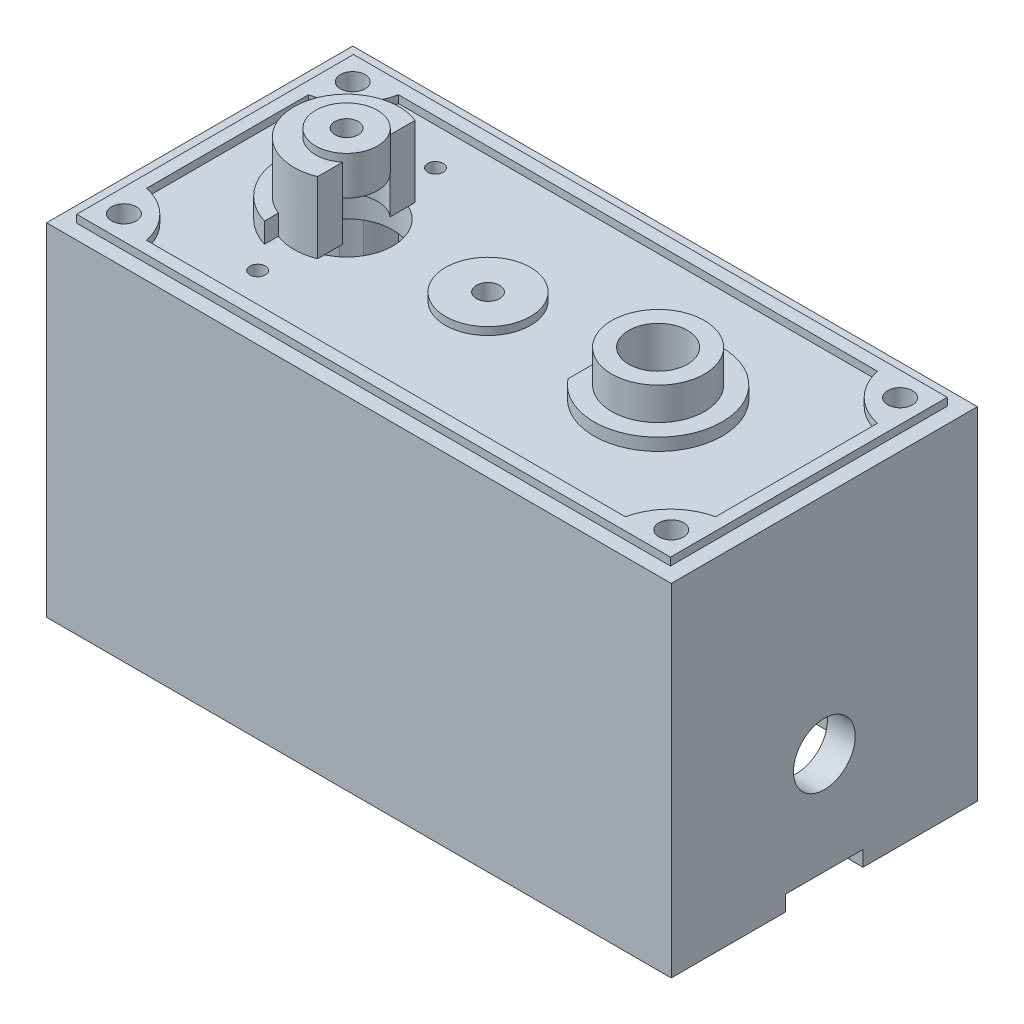
SolidWorks part; units mm, degrees
ref_plane "前基準面" through (0, 0, 0) normal (0, 0, 1) x (1, 0, 0)
ref_plane "上基準面" through (0, 0, 0) normal (0, 1, 0) x (1, 0, 0)
ref_plane "右基準面" through (0, 0, 0) normal (1, 0, 0) x (0, 0, -1)
sketch "草圖1" plane through (0, 0, 0) normal (0, 0, 1) x (1, 0, 0)
  line L1 (-20.2, 10.8) -> (20.2, 10.8)
  line L2 (-20.2, 10.8) -> (-20.2, -10.8)
  line L3 (-20.2, -10.8) -> (20.2, -10.8)
  line L4 (20.2, 10.8) -> (20.2, -10.8)
  line L5 (-20.2, 10.8) -> (20.2, -10.8) construction
  line L6 (-20.2, -10.8) -> (20.2, 10.8) construction
  point P0 (0, 0)
  dimension "D1" = 40.4
  dimension "D2" = 21.6
extrude "伸長1" add sketch "草圖1" along normal blind 19.8
sketch "草圖3" plane through (0, 10.8, 0) normal (0, 1, 0) x (1, 0, 0)
  line L0 (0, 0) -> (0, -19.8) construction
  line L1 (-19.2, -0.95) -> (19.2, -0.95)
  line L2 (-19.2, -0.95) -> (-19.2, -18.85)
  line L3 (-19.2, -18.85) -> (19.2, -18.85)
  line L4 (19.2, -0.95) -> (19.2, -18.85)
  line L5 (-19.2, -0.95) -> (19.2, -18.85) construction
  line L6 (-19.2, -18.85) -> (19.2, -0.95) construction
  line L7 (20.2, 0) -> (-20.2, 0) construction
  line L8 (20.2, -19.8) -> (-20.2, -19.8) construction
  line L9 (20.2, -9.9) -> (-20.2, -9.9) construction
  line L10 (20.2, -19.8) -> (20.2, 0) construction
  line L11 (-20.2, -19.8) -> (-20.2, 0) construction
  line L12 (-15.4852, -1.75) -> (15.4852, -1.75)
  line L13 (-15.4852, -18.05) -> (15.4852, -18.05)
  line L14 (-18.4, -4.6648) -> (-18.4, -15.1352)
  line L16 (18.4, -4.6648) -> (18.4, -15.1352)
  arc A0 (-18.4, -4.6648) -> (-15.4852, -1.75) centre (-19.2, -0.95) ccw
  arc A1 (-18.4, -15.1352) -> (-15.4852, -18.05) centre (-19.2, -18.85) cw
  arc A2 (15.4852, -1.75) -> (18.4, -4.6648) centre (19.2, -0.95) ccw
  arc A3 (18.4, -15.1352) -> (15.4852, -18.05) centre (19.2, -18.85) ccw
  point P0 (0, -9.9)
  point P17 (0, -9.9)
  dimension "D5" = 3.8
  dimension "D1" = 38.4
  dimension "D2" = 17.9
  dimension "D3" = 0.8
  dimension "D4" = 0.8
  dimension "D6" = 0.8
  dimension "D7" = 0.8
extrude "伸長2" add sketch "草圖3" along normal blind 1
sketch "草圖4" plane through (0, 10.8, 0) normal (0, 1, 0) x (1, 0, 0)
  line L4 (20.2, 0) -> (-20.2, 0)
  line L5 (20.2, 0) -> (-20.2, 0)
  line L6 (-20.2, 0) -> (-20.2, -19.8)
  line L7 (-20.2, 0) -> (-20.2, -19.8)
  line L8 (-20.2, -19.8) -> (20.2, -19.8)
  line L9 (-20.2, -19.8) -> (20.2, -19.8)
  line L10 (20.2, -19.8) -> (20.2, 0)
  line L11 (20.2, -19.8) -> (20.2, 0)
  dimension "D1" = 0
extrude "伸長3" add sketch "草圖4" along normal blind 0.5
sketch "草圖5" plane through (0, 11.3, 0) normal (0, 1, 0) x (1, 0, 0)
  line L0 (-20.2, -9.9) -> (20.2, -9.9) construction
  line L1 (-20.2, 0) -> (-20.2, -19.8) construction
  line L2 (20.2, -19.8) -> (20.2, 0) construction
  line L3 (19.2, -18.85) -> (19.2, -0.95) construction
  circle A0 centre (-1.55, -9.9) radius 2.75
  dimension "D1" = 5.5
  dimension "D3" = 20.75
sketch "草圖6" plane through (0, 11.3, 0) normal (0, 1, 0) x (1, 0, 0)
  line L0 (6.2, -7.3193) -> (6.2, -12.4807)
  line L1 (-20.2, -9.9) -> (20.2, -9.9) construction
  line L3 (19.2, -18.85) -> (19.2, -0.95) construction
  arc A0 (6.2, -12.4807) -> (6.2, -7.3193) centre (9.45, -9.9) ccw
  dimension "D1" = 4.15
  dimension "D2" = 3.25
  dimension "D3" = 13
extrude "伸長4" add sketch "草圖5" along normal blind 0.5
extrude "伸長5" add sketch "草圖6" along normal blind 0.8
sketch "草圖7" plane through (0, 12.1, 0) normal (0, 1, 0) x (1, 0, 0)
  circle A0 centre (9.45, -9.9) radius 3
  dimension "D1" = 6
extrude "伸長6" add sketch "草圖7" along normal blind 2.1
sketch "草圖8" plane through (0, 14.2, 0) normal (0, 1, 0) x (1, 0, 0)
  circle A0 centre (9.45, -9.9) radius 1.9
  dimension "D1" = 3.8
extrude "伸長7" cut sketch "草圖8" against normal through all
sketch "草圖10" plane through (0, 11.8, 0) normal (0, 1, 0) x (1, 0, 0)
  circle A0 centre (-1.55, -9.9) radius 0.75
  dimension "D1" = 1.5
extrude "伸長10" cut sketch "草圖10" against normal blind 2.7
sketch "草圖11" plane through (0, 11.3, 0) normal (0, 1, 0) x (1, 0, 0)
  line L0 (-10.7, -9.9) -> (-20.2, -9.9) construction
  line L1 (-20.2, 0) -> (-20.2, -19.8) construction
  line L4 (-11.95, -5.838) -> (-11.95, -13.962)
  arc A0 (-11.95, -5.838) -> (-11.95, -13.962) centre (-10.7, -9.9) ccw
  dimension "D1" = 8.5
  dimension "D2" = 9.5
  dimension "D3" = 8.124
extrude "伸長11" add sketch "草圖11" along normal blind 1.3
sketch "草圖13" plane through (0, 12.6, 0) normal (0, 1, 0) x (1, 0, 0)
  circle A0 centre (-10.7, -9.9) radius 3
  dimension "D1" = 6
extrude "伸長13" cut sketch "草圖13" against normal through all
sketch "草圖12" plane through (0, 12.6, 0) normal (0, 1, 0) x (1, 0, 0)
  line L0 (-9.4204, -6.75) -> (-9.4204, -13.05)
  arc A0 (-9.4204, -6.75) -> (-9.4204, -13.05) centre (-10.7, -9.9) ccw
  dimension "D1" = 6.8
  dimension "D2" = 6.3
extrude "伸長14" add sketch "草圖12" along normal blind 3.3 and the other way up to surface
sketch "草圖14" plane through (0, 15.9, 0) normal (0, 1, 0) x (1, 0, 0)
  circle A0 centre (-10.7, -9.9) radius 2
  dimension "D1" = 4
extrude "伸長15" cut sketch "草圖14" against normal through all
sketch "草圖15" plane through (0, 15.9, 0) normal (0, 1, 0) x (1, 0, 0)
  circle A0 centre (-10.7, -9.9) radius 2
  dimension "D1" = 4
extrude "伸長16" add sketch "草圖15" along normal blind 0.5 and the other way blind 2
sketch "草圖16" plane through (0, 16.4, 0) normal (0, 1, 0) x (1, 0, 0)
  circle A0 centre (-10.7, -9.9) radius 0.75
  dimension "D1" = 1.5
extrude "伸長17" cut sketch "草圖16" against normal blind 2.3
sketch "草圖17" plane through (0, -10.8, 0) normal (0, -1, 0) x (1, 0, 0)
  line L0 (-20.2, 19.8) -> (20.2, 19.8) construction
  line L1 (19.3, 0.9) -> (-19.3, 0.9)
  line L2 (19.3, 0.9) -> (19.3, 18.9)
  line L3 (19.3, 18.9) -> (-19.3, 18.9)
  line L4 (-19.3, 0.9) -> (-19.3, 18.9)
  line L5 (20.2, 19.8) -> (20.2, 0) construction
  line L6 (-20.2, 0) -> (20.2, 0) construction
  line L7 (-20.2, 19.8) -> (-20.2, 0) construction
  dimension "D1" = 0.9
  dimension "D2" = 0.9
  dimension "D3" = 0.9
  dimension "D4" = 0.9
extrude "伸長18" cut sketch "草圖17" against normal blind 20
sketch "草圖18" plane through (0, 9.2, 0) normal (0, -1, 0) x (1, 0, 0)
  line L0 (15.4852, 1.75) -> (-15.4852, 1.75) construction
  line L1 (-18.4, 4.6648) -> (-18.4, 15.1352) construction
  line L2 (18.4, 15.1352) -> (18.4, 4.6648) construction
  line L3 (-15.4852, 18.05) -> (15.4852, 18.05) construction
  line L4 (-19.3, 0.9) -> (19.3, 0.9) construction
  line L5 (-19.3, 18.9) -> (-19.3, 0.9) construction
  line L6 (19.3, 18.9) -> (-19.3, 18.9) construction
  line L7 (19.3, 0.9) -> (19.3, 18.9) construction
  line L8 (-19.3, 0.9) -> (19.3, 0.9)
  line L9 (-19.3, 18.9) -> (-19.3, 0.9)
  line L10 (19.3, 18.9) -> (-19.3, 18.9)
  line L11 (19.3, 0.9) -> (19.3, 18.9)
  line L12 (15.4852, 1.75) -> (-15.4852, 1.75)
  line L13 (-18.4, 4.6648) -> (-18.4, 15.1352)
  line L14 (18.4, 15.1352) -> (18.4, 4.6648)
  line L15 (-15.4852, 18.05) -> (15.4852, 18.05)
  arc A0 (-15.4852, 1.75) -> (-18.4, 4.6648) centre (-19.2, 0.95) ccw construction
  arc A1 (-18.4, 15.1352) -> (-15.4852, 18.05) centre (-19.2, 18.85) ccw construction
  arc A2 (18.4, 4.6648) -> (15.4852, 1.75) centre (19.2, 0.95) ccw construction
  arc A3 (15.4852, 18.05) -> (18.4, 15.1352) centre (19.2, 18.85) ccw construction
  arc A4 (-15.4852, 1.75) -> (-18.4, 4.6648) centre (-19.2, 0.95) ccw
  arc A5 (-18.4, 15.1352) -> (-15.4852, 18.05) centre (-19.2, 18.85) ccw
  arc A6 (18.4, 4.6648) -> (15.4852, 1.75) centre (19.2, 0.95) ccw
  arc A7 (15.4852, 18.05) -> (18.4, 15.1352) centre (19.2, 18.85) ccw
  point P14 (-28.1205, 7.0826)
extrude "伸長19" add sketch "草圖18" along normal blind 18
sketch "草圖19" plane through (0, 11.8, 0) normal (0, 1, 0) x (1, 0, 0)
  line L0 (20.2, 0) -> (-20.2, 0) construction
  line L1 (-17.7, -2.5) -> (17.7, -2.5) construction
  line L2 (-17.7, -2.5) -> (-17.7, -17.3) construction
  line L3 (-17.7, -17.3) -> (17.7, -17.3) construction
  line L4 (17.7, -2.5) -> (17.7, -17.3) construction
  line L5 (-17.7, -2.5) -> (17.7, -17.3) construction
  line L6 (-17.7, -17.3) -> (17.7, -2.5) construction
  line L7 (20.2, -19.8) -> (20.2, 0) construction
  line L8 (0, 0) -> (0, -19.8) construction
  line L9 (-20.2, -19.8) -> (20.2, -19.8) construction
  line L10 (20.2, -9.9) -> (-20.2, -9.9) construction
  line L11 (-20.2, 0) -> (-20.2, -19.8) construction
  circle A0 centre (-17.7, -2.5) radius 0.8
  circle A1 centre (17.7, -2.5) radius 0.8
  circle A2 centre (17.7, -17.3) radius 0.8
  circle A3 centre (-17.7, -17.3) radius 0.8
  point P0 (0, -9.9)
  dimension "D3" = 1.6
  dimension "D1" = 2.5
  dimension "D2" = 2.5
extrude "伸長20" cut sketch "草圖19" against normal blind 27.4
sketch "草圖20" plane through (0, 9.2, 0) normal (0, -1, 0) x (1, 0, 0)
  circle A0 centre (-10.7, 9.9) radius 8.6
  dimension "D1" = 17.2
extrude "伸長21" cut sketch "草圖20" along normal blind 27.4
sketch "草圖21" plane through (0, 9.2, 0) normal (0, -1, 0) x (1, 0, 0)
  circle A0 centre (-1.55, 9.9) radius 1.05
  dimension "D1" = 2.1
extrude "伸長22" add sketch "草圖21" along normal blind 0.5
sketch "草圖22" plane through (0, 9.2, 0) normal (0, 1, 0) x (1, 0, 0)
  circle A0 centre (-1.55, -9.9) radius 0.75 construction
  circle A1 centre (-1.55, -9.9) radius 0.75
extrude "伸長23" cut sketch "草圖22" against normal blind 0.1
sketch "草圖23" plane through (0, 11.3, 0) normal (0, 1, 0) x (1, 0, 0)
  line L0 (-10.7, -15.65) -> (-10.7, -4.15) construction
  circle A1 centre (-10.7, -4.15) radius 0.5
  circle A2 centre (-10.7, -15.65) radius 0.5
  point P3 (-10.7, -9.9)
  dimension "D2" = 1
  dimension "D1" = 11.5
extrude "伸長24" cut sketch "草圖23" against normal up to next
sketch "草圖25" plane through (20.2, 0, 0) normal (1, 0, 0) x (0, 0, -1)
  line L0 (-9.9, -10.8) -> (-9.9, 11.3) construction
  line L1 (-7.4, -9.8) -> (-12.4, -9.8)
  line L2 (-7.4, -9.8) -> (-7.4, -10.8)
  line L3 (-7.4, -10.8) -> (-12.4, -10.8)
  line L4 (-12.4, -9.8) -> (-12.4, -10.8)
  line L5 (-7.4, -9.8) -> (-12.4, -10.8) construction
  line L6 (-7.4, -10.8) -> (-12.4, -9.8) construction
  line L7 (-19.8, 11.3) -> (0, 11.3) construction
  line L8 (-19.8, -10.8) -> (0, -10.8) construction
  circle A0 centre (-9.9, -3.2) radius 2
  point P4 (-9.9, -10.3)
  dimension "D1" = 4
  dimension "D2" = 1
  dimension "D3" = 5
  dimension "D4" = 14.5
extrude "伸長27" cut sketch "草圖25" against normal up to surface (1.8 mm away) up to face at (18.4, 0.2, 9.9)
